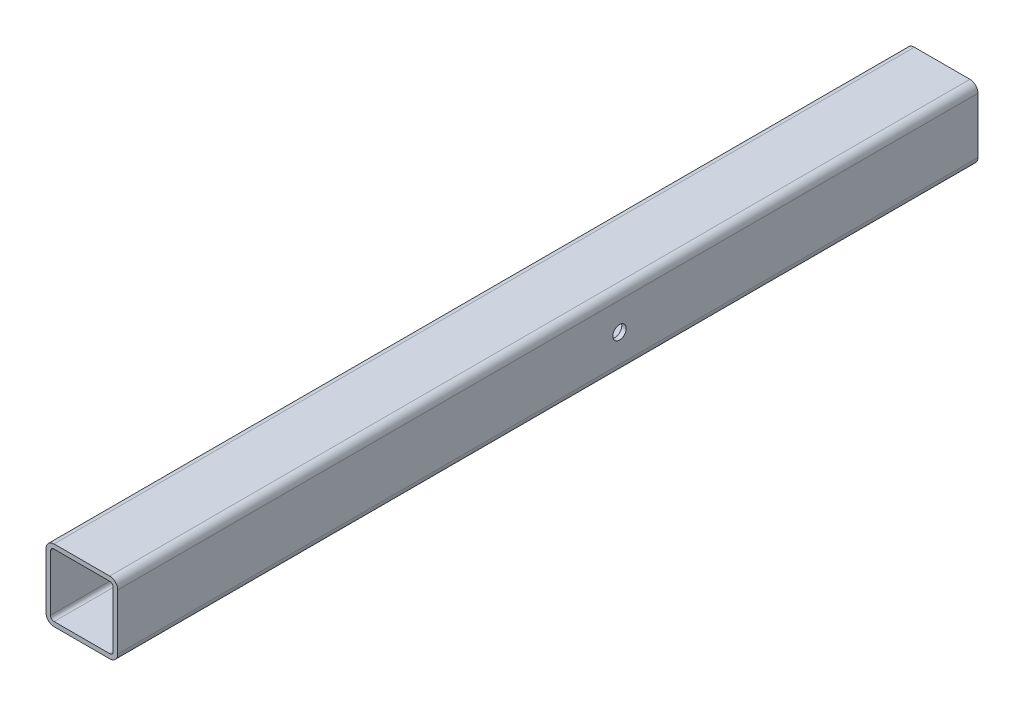
SolidWorks part; units mm, degrees
ref_plane "Front Plane" through (0, 0, 0) normal (0, 0, 1) x (1, 0, 0)
ref_plane "Top Plane" through (0, 0, 0) normal (0, 1, 0) x (1, 0, 0)
ref_plane "Right Plane" through (0, 0, 0) normal (1, 0, 0) x (0, 0, -1)
sketch "Sketch1" plane through (0, 0, 0) normal (0, 0, 1) x (1, 0, 0)
  line L0 (-19.685, 25.4) -> (19.685, 25.4)
  line L1 (-19.685, -22.225) -> (19.685, -22.225)
  line L2 (-22.225, -19.685) -> (-22.225, 19.685)
  line L3 (-19.685, 22.225) -> (19.685, 22.225)
  line L4 (22.225, -19.685) -> (22.225, 19.685)
  line L5 (-22.225, -22.225) -> (22.225, 22.225) construction
  line L6 (-22.225, 22.225) -> (22.225, -22.225) construction
  line L7 (25.4, -19.685) -> (25.4, 19.685)
  line L8 (-19.685, -25.4) -> (19.685, -25.4)
  line L9 (-25.4, -19.685) -> (-25.4, 19.685)
  arc A0 (-19.685, -22.225) -> (-22.225, -19.685) centre (-19.685, -19.685) cw
  arc A1 (19.685, -22.225) -> (22.225, -19.685) centre (19.685, -19.685) ccw
  arc A2 (19.685, 22.225) -> (22.225, 19.685) centre (19.685, 19.685) cw
  arc A3 (-22.225, 19.685) -> (-19.685, 22.225) centre (-19.685, 19.685) cw
  arc A4 (19.685, 25.4) -> (25.4, 19.685) centre (19.685, 19.685) cw
  arc A5 (19.685, -25.4) -> (25.4, -19.685) centre (19.685, -19.685) ccw
  arc A6 (-19.685, -25.4) -> (-25.4, -19.685) centre (-19.685, -19.685) cw
  arc A7 (-25.4, 19.685) -> (-19.685, 25.4) centre (-19.685, 19.685) cw
  point P0 (0, 0)
  dimension "D3" = 2.54
  dimension "D1" = 44.45
  dimension "D2" = 44.45
  dimension "D4" = 3.175
extrude "Boss-Extrude1" add sketch "Sketch1" along normal mid plane 609.6
sketch "Sketch3" plane through (25.4, 0, 0) normal (1, 0, 0) x (0, 0, -1)
  line L0 (-365.1722, 0) -> (365.1722, 0) construction
  line L1 (0, -124.3491) -> (0, 124.3491) construction
  line L2 (101.6, -102.615) -> (101.6, 102.615) construction
  line L3 (50.8, -89.9368) -> (50.8, 89.9368) construction
  line L4 (304.8, -19.685) -> (304.8, 19.685) construction
  circle A0 centre (50.8, 0) radius 4.7625
  point P4 (0, 0)
  point P8 (0, 0)
  point P11 (101.6, 0)
  point P14 (50.8, 0)
  point P20 (228.6, 0)
  dimension "D3" = 9.525
  dimension "D1" = 203.2
  dimension "D2" = 50.8
extrude "Cut-Extrude2" cut sketch "Sketch3" against normal blind 76.2
